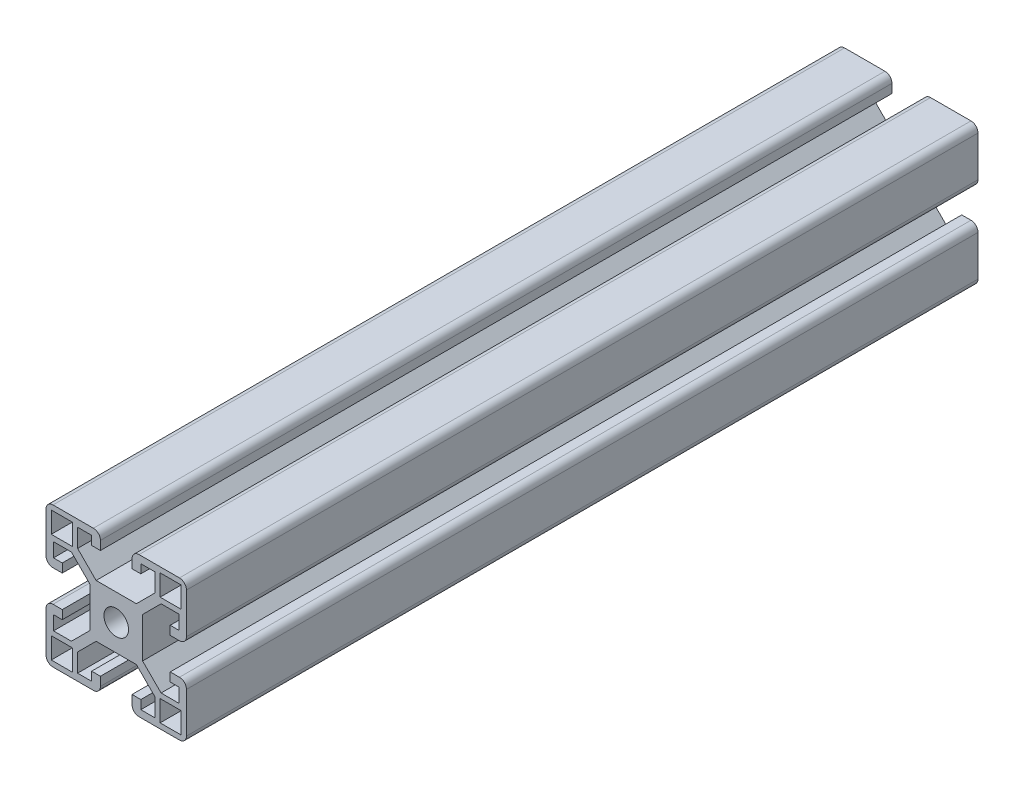
SolidWorks part; units mm, degrees
ref_plane "Alzado" through (0, 0, 0) normal (0, 0, 1) x (1, 0, 0)
ref_plane "Planta" through (0, 0, 0) normal (0, 1, 0) x (1, 0, 0)
ref_plane "Vista lateral" through (0, 0, 0) normal (1, 0, 0) x (0, 0, -1)
sketch "Croquis1" plane through (0, 0, 0) normal (0, 0, 1) x (1, 0, 0)
  line L1 (-20, -20) -> (20, -20)
  line L2 (-20, -20) -> (-20, 20)
  line L3 (-20, 20) -> (20, 20)
  line L4 (20, -20) -> (20, 20)
  line L5 (-20, -20) -> (20, 20) construction
  line L6 (-20, 20) -> (20, -20) construction
  point P0 (0, 0)
  dimension "D1" = 40
  dimension "D2" = 40
extrude "Saliente-Extruir1" add sketch "Croquis1" along normal blind 225.4
sketch "Croquis2" plane through (0, 0, 225.4) normal (0, 0, 1) x (1, 0, 0)
  line L0 (-7.5, 7.5) -> (-20, 20) construction
  line L1 (5.7336, -7.5014) -> (-5.7336, -7.5014)
  line L2 (7.5013, -5.7336) -> (7.5013, 5.7336)
  line L3 (5.7336, 7.5014) -> (-5.7336, 7.5014)
  line L4 (-7.5013, -5.7336) -> (-7.5013, 5.7336)
  line L5 (7.5, -7.5) -> (-7.5, 7.5) construction
  line L6 (7.5, 7.5) -> (-7.5, -7.5) construction
  line L7 (-5.7336, 7.5014) -> (-11, 12.7678)
  line L8 (-7.5013, 5.7336) -> (-12.7678, 11)
  line L9 (-20, 20) -> (-20, -20) construction
  line L10 (-18.5, 12.5) -> (-12.5, 12.5)
  line L11 (-18.5, 12.5) -> (-18.5, 18.5)
  line L12 (-18.5, 18.5) -> (-12.5, 18.5)
  line L13 (-12.5, 12.5) -> (-12.5, 18.5)
  line L14 (-18.5, 12.5) -> (-12.5, 18.5) construction
  line L15 (-18.5, 18.5) -> (-12.5, 12.5) construction
  line L16 (-11, 12.7678) -> (-11, 18)
  line L17 (-11, 18) -> (-7, 18)
  line L18 (-7, 18) -> (-7, 15.5)
  line L19 (-7, 15.5) -> (-4.5, 15.5)
  line L20 (-4.5, 15.5) -> (-4.5, 20)
  line L21 (20, 20) -> (-20, 20) construction
  line L22 (0, 20) -> (0, -20) construction
  line L23 (-20, -20) -> (20, -20) construction
  line L24 (-12.7678, 11) -> (-17.8676, 11)
  line L25 (-17.8676, 11) -> (-17.8676, 7)
  line L26 (-17.8676, 7) -> (-15.3676, 7)
  line L27 (-15.3676, 7) -> (-15.3676, 4.5)
  line L28 (-15.3676, 4.5) -> (-20, 4.5)
  line L29 (18.5, 18.5) -> (12.5, 12.5) construction
  line L30 (18.5, 12.5) -> (12.5, 18.5) construction
  line L31 (7.5, 7.5) -> (20, 20) construction
  line L32 (15.3676, 4.5) -> (20, 4.5)
  line L33 (15.3676, 7) -> (15.3676, 4.5)
  line L34 (17.8676, 7) -> (15.3676, 7)
  line L35 (17.8676, 11) -> (17.8676, 7)
  line L36 (12.7678, 11) -> (17.8676, 11)
  line L37 (4.5, 15.5) -> (4.5, 20)
  line L38 (7, 15.5) -> (4.5, 15.5)
  line L39 (7, 18) -> (7, 15.5)
  line L40 (11, 18) -> (7, 18)
  line L41 (11, 12.7678) -> (11, 18)
  line L42 (12.5, 12.5) -> (12.5, 18.5)
  line L43 (18.5, 18.5) -> (12.5, 18.5)
  line L44 (18.5, 12.5) -> (18.5, 18.5)
  line L45 (18.5, 12.5) -> (12.5, 12.5)
  line L46 (7.5013, 5.7336) -> (12.7678, 11)
  line L47 (5.7336, 7.5014) -> (11, 12.7678)
  line L48 (20, 0) -> (-20, 0) construction
  line L49 (20, -20) -> (20, 20) construction
  line L50 (7.5, -7.5) -> (20, -20) construction
  line L51 (18.5, -12.5) -> (12.5, -18.5) construction
  line L52 (18.5, -18.5) -> (12.5, -12.5) construction
  line L53 (-18.5, -18.5) -> (-12.5, -12.5) construction
  line L54 (-18.5, -12.5) -> (-12.5, -18.5) construction
  line L55 (-7.5, -7.5) -> (-20, -20) construction
  line L56 (5.7336, -7.5014) -> (11, -12.7678)
  line L57 (7.5013, -5.7336) -> (12.7678, -11)
  line L58 (18.5, -12.5) -> (12.5, -12.5)
  line L59 (18.5, -12.5) -> (18.5, -18.5)
  line L60 (18.5, -18.5) -> (12.5, -18.5)
  line L61 (12.5, -12.5) -> (12.5, -18.5)
  line L62 (11, -12.7678) -> (11, -18)
  line L63 (11, -18) -> (7, -18)
  line L64 (7, -18) -> (7, -15.5)
  line L65 (7, -15.5) -> (4.5, -15.5)
  line L66 (4.5, -15.5) -> (4.5, -20)
  line L67 (12.7678, -11) -> (17.8676, -11)
  line L68 (17.8676, -11) -> (17.8676, -7)
  line L69 (17.8676, -7) -> (15.3676, -7)
  line L70 (15.3676, -7) -> (15.3676, -4.5)
  line L71 (15.3676, -4.5) -> (20, -4.5)
  line L72 (-15.3676, -4.5) -> (-20, -4.5)
  line L73 (-15.3676, -7) -> (-15.3676, -4.5)
  line L74 (-17.8676, -7) -> (-15.3676, -7)
  line L75 (-17.8676, -11) -> (-17.8676, -7)
  line L76 (-12.7678, -11) -> (-17.8676, -11)
  line L77 (-4.5, -15.5) -> (-4.5, -20)
  line L78 (-7, -15.5) -> (-4.5, -15.5)
  line L79 (-7, -18) -> (-7, -15.5)
  line L80 (-11, -18) -> (-7, -18)
  line L81 (-11, -12.7678) -> (-11, -18)
  line L82 (-12.5, -12.5) -> (-12.5, -18.5)
  line L83 (-18.5, -18.5) -> (-12.5, -18.5)
  line L84 (-18.5, -12.5) -> (-18.5, -18.5)
  line L85 (-18.5, -12.5) -> (-12.5, -12.5)
  line L86 (-7.5013, -5.7336) -> (-12.7678, -11)
  line L87 (-5.7336, -7.5014) -> (-11, -12.7678)
  line L88 (5.7336, -7.5014) -> (-5.7336, -7.5014)
  line L89 (-20, -4.5) -> (-20, 4.5)
  line L90 (20, 4.5) -> (20, -4.5)
  line L91 (-4.5, -20) -> (4.5, -20)
  line L92 (-4.5, 20) -> (4.5, 20)
  circle A0 centre (0, 0) radius 3.5
  point P0 (0, 0)
  point P14 (-15.5, 15.5)
  point P56 (15.5, 15.5)
  point P99 (15.5, -15.5)
  point P100 (-15.5, -15.5)
  line M20 (20, -20) -> (20, 20)
  line M21 (20, 20) -> (-20, 20)
  line M22 (-20, 20) -> (-20, -20)
  line M23 (-20, -20) -> (20, -20)
  dimension "D3" = 7
  dimension "D1" = 15
  dimension "D2" = 15
  dimension "D4" = 1.25
  dimension "D5" = 1.25
  dimension "D6" = 1.5
  dimension "D7" = 6
  dimension "D8" = 6
  dimension "D9" = 1.5
  dimension "D10" = 2
  dimension "D11" = 4
  dimension "D12" = 2.5
  dimension "D13" = 2.5
  dimension "D14" = 1.5
  dimension "D15" = 4
  dimension "D16" = 2.5
  dimension "D17" = 2.5
extrude "Cortar-Extruir2" cut sketch "Croquis2" against normal up to surface (225.4 mm away) contours L10 L13 L12 L11 | L3 L47 L41 L40 L39 L38 L37 L20 L19 L18 L17 L16 L7 M21 | L45 L44 L43 L42 | L70 L71 L32 L33 L34 L35 L36 L46 L2 L57 L67 L68 L69 M20 | L86 L4 L8 L24 L25 L26 L27 L28 L72 L73 L74 L75 L76 M22 | A0 | L1 L87 L81 L80 L79 L78 L77 L66 L65 L64 L63 L62 L56 M23 | L85 L84 L83 L82 | L58 L61 L60 L59 up to face at (0, 0, 0)
fillet "Redondeo1" radius 2 4 edges at (-20, -20, 112.7) (-20, 20, 112.7) (20, -20, 112.7) (20, 20, 112.7)
fillet "Redondeo2" radius 2 8 edges at (-20, -4.5, 112.7) (-20, 4.5, 112.7) (-4.5, -20, 112.7) (4.5, -20, 112.7) (20, 4.5, 112.7) (20, -4.5, 112.7) (4.5, 20, 112.7) (-4.5, 20, 112.7)
